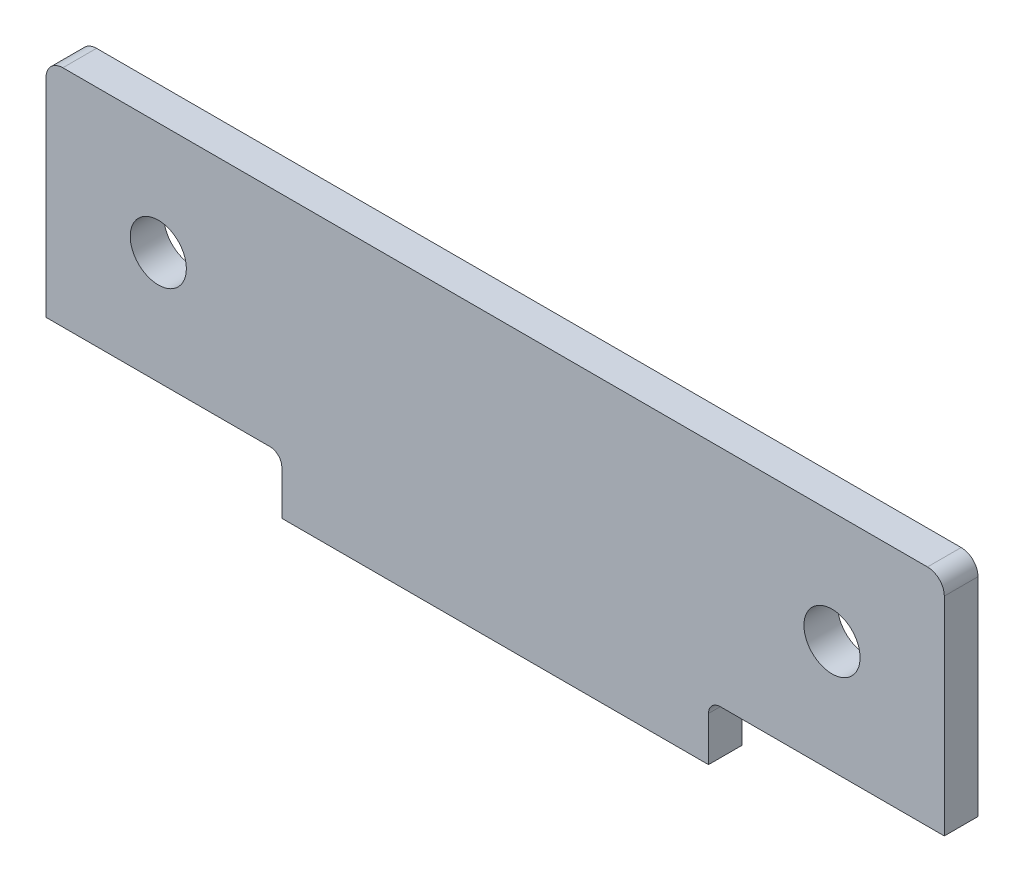
SolidWorks part; units mm, degrees
ref_plane "正面" through (0, 0, 0) normal (0, 0, 1) x (1, 0, 0)
ref_plane "平面" through (0, 0, 0) normal (0, 1, 0) x (1, 0, 0)
ref_plane "右側面" through (0, 0, 0) normal (1, 0, 0) x (0, 0, -1)
sketch "ｽｹｯﾁ1" plane through (0, 0, 0) normal (0, 0, 1) x (1, 0, 0)
  line L0 (-19, 0) -> (19, 0)
  line L1 (0, 0) -> (0, 25) construction
  line L2 (40, 25) -> (-40, 25)
  line L3 (-40, 25) -> (-40, 5)
  line L4 (-40, 5) -> (-19, 5)
  line L5 (-19, 5) -> (-19, 0)
  line L7 (19, 5) -> (40, 25) construction
  line L8 (19, 5) -> (19, 0)
  line L9 (40, 5) -> (19, 5)
  line L10 (40, 25) -> (40, 5)
  circle A0 centre (-30, 15) radius 2.5
  circle A1 centre (30, 15) radius 2.5
  dimension "D5" = 5
  dimension "D1" = 20
  dimension "D2" = 40
  dimension "D3" = 21
  dimension "D4" = 5
  dimension "D6" = 10
  dimension "D7" = 10
extrude "ﾎﾞｽ - 押し出し1" add sketch "ｽｹｯﾁ1" along normal blind 3
fillet "ﾌｨﾚｯﾄ1" radius 1.05 2 edges at (19, 5, 1.5) (-19, 5, 1.5)
fillet "ﾌｨﾚｯﾄ2" radius 1.5 2 edges at (40, 25, 1.5) (-40, 25, 1.5)
